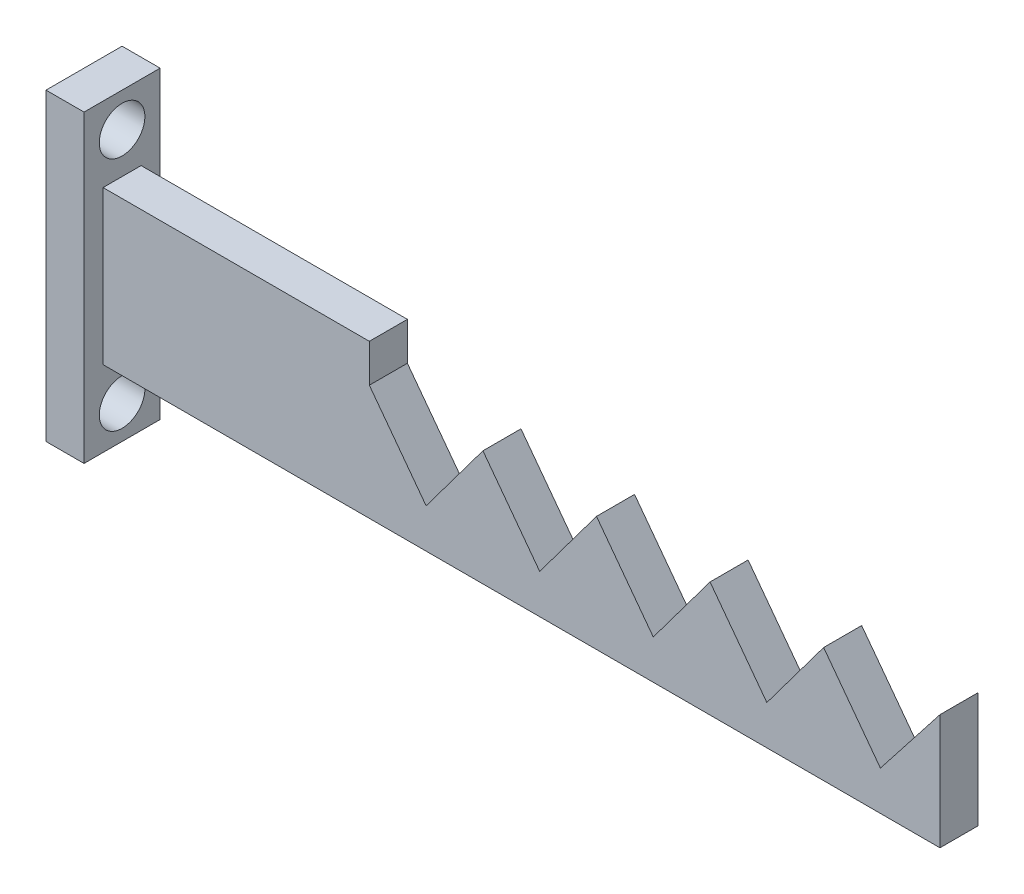
SolidWorks part; units mm, degrees
ref_plane "Front Plane" through (0, 0, 0) normal (0, 0, 1) x (1, 0, 0)
ref_plane "Top Plane" through (0, 0, 0) normal (0, 1, 0) x (1, 0, 0)
ref_plane "Right Plane" through (0, 0, 0) normal (1, 0, 0) x (0, 0, -1)
sketch "Sketch1" plane through (0, 0, 0) normal (0, 0, 1) x (1, 0, 0)
  line L0 (55, 0) -> (-55, 0) construction
  line L2 (-8.89, 0) -> (-8.89, 7.62)
  line L3 (-8.89, 7.62) -> (8.89, 7.62)
  line L6 (8.89, 5.08) -> (12.6816, 0)
  line L7 (12.6816, 0) -> (16.4732, 5.08)
  line L8 (16.4732, 5.08) -> (20.2648, 0)
  line L9 (20.2648, 0) -> (24.0564, 5.08)
  line L10 (24.0564, 5.08) -> (27.848, 0)
  line L11 (27.848, 0) -> (31.6396, 5.08)
  line L12 (46.99, 5.08) -> (8.89, 5.08) construction
  line L13 (31.6396, 5.08) -> (35.4312, 0)
  line L14 (35.4312, 0) -> (39.2228, 5.08)
  line L15 (39.2228, 5.08) -> (43.0144, 0)
  line L16 (43.0144, 0) -> (46.99, 5.08)
  line L17 (46.99, 5.08) -> (46.99, 0)
  line L19 (8.89, 5.08) -> (8.89, 7.62)
  line L20 (-8.89, 0) -> (-8.89, -2.6204)
  line L21 (-8.89, -2.6204) -> (46.99, -2.6204)
  line L22 (46.99, -2.6204) -> (46.99, 0)
  point P1 (0, 0)
  point P6 (0, 7.62)
  point P10 (0, 0)
  point P22 (0, 0)
  dimension "D1" = 7.62
  dimension "D2" = 53.263
  dimension "D3" = 10.2404
  dimension "D4" = 51.953
  dimension "D5" = 17.78
  dimension "D6" = 7.5832
  dimension "D7" = 2.6204
extrude "Boss-Extrude1" add sketch "Sketch1" along normal blind 2.54
sketch "Sketch2" plane through (-8.89, 0, 0) normal (-1, 0, 0) x (0, 0, 1)
  line L0 (2.54, 7.62) -> (2.54, -2.6204) construction
  line L1 (-1.27, 12.6196) -> (3.81, 12.6196)
  line L2 (-1.27, 12.6196) -> (-1.27, -7.7004)
  line L3 (-1.27, -7.7004) -> (3.81, -7.7004)
  line L4 (3.81, 12.6196) -> (3.81, -7.7004)
  line L5 (-1.27, 12.6196) -> (3.81, -7.7004) construction
  line L6 (-1.27, -7.7004) -> (3.81, 12.6196) construction
  line L7 (2.54, -2.6204) -> (0, -2.6204) construction
  point P0 (1.27, 2.4596)
  dimension "D1" = 20.32
  dimension "D2" = 5.08
  dimension "D3" = 1.27
  dimension "D4" = 5.08
extrude "Boss-Extrude2" add sketch "Sketch2" along normal blind 2.54
sketch "Sketch3" plane through (-11.43, 0, 0) normal (-1, 0, 0) x (0, 0, 1)
  line L0 (-8.4214, 2.4596) -> (5.8814, 2.4596) construction
  line L2 (1.27, -29.1059) -> (1.27, 13.0434) construction
  line L4 (3.81, 12.6196) -> (-1.27, 12.6196) construction
  line L5 (-1.27, 12.6196) -> (-1.27, -7.7004) construction
  line L6 (-1.27, -7.7004) -> (3.81, -7.7004) construction
  circle A0 centre (1.27, 10.3336) radius 1.524
  circle A1 centre (1.27, -5.4144) radius 1.524
  point P3 (1.27, 10.3336)
  point P6 (1.27, -8.0313)
  point P18 (6.0695, -7.4988)
  dimension "D1" = 3.048
  dimension "D2" = 2.286
  dimension "D3" = 2.54
  dimension "D4" = 2.286
extrude "Cut-Extrude1" cut sketch "Sketch3" against normal blind 2.54
